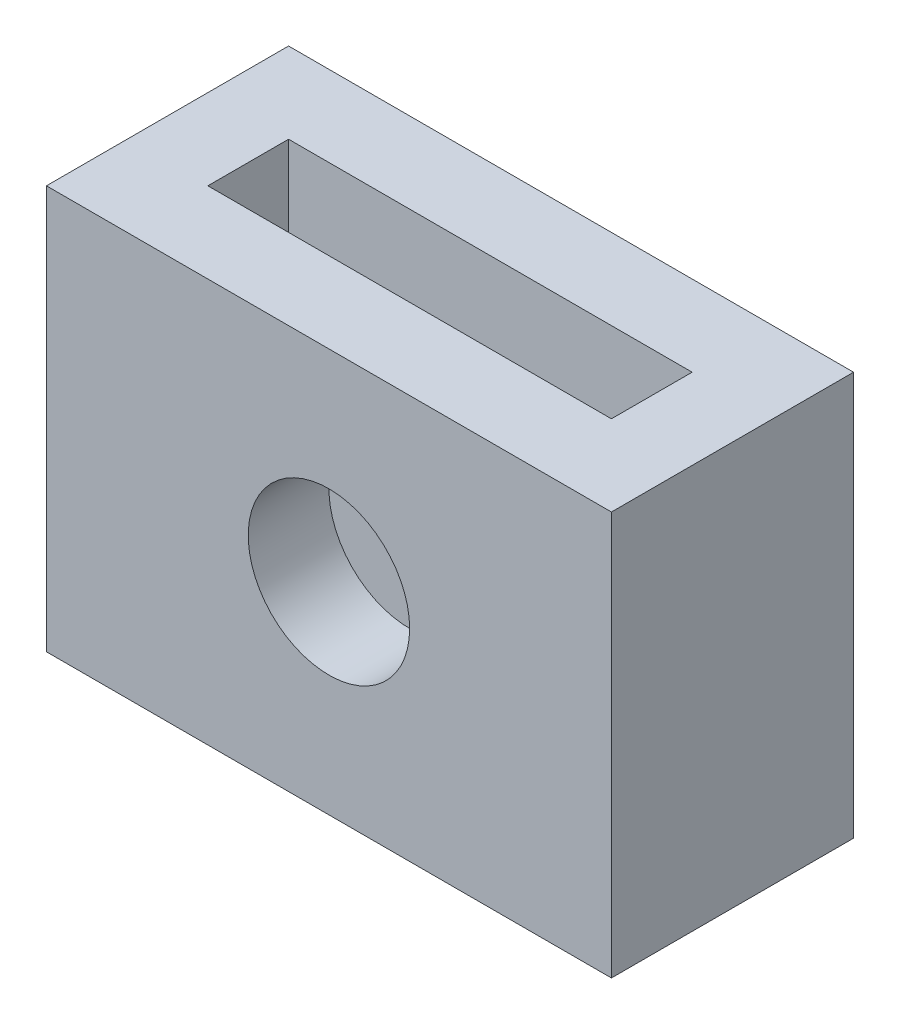
SolidWorks part; units mm, degrees
ref_plane "Alzado" through (0, 0, 0) normal (0, 0, 1) x (1, 0, 0)
ref_plane "Planta" through (0, 0, 0) normal (0, 1, 0) x (1, 0, 0)
ref_plane "Vista lateral" through (0, 0, 0) normal (1, 0, 0) x (0, 0, -1)
sketch "Croquis1" plane through (0, 0, 0) normal (0, 0, 1) x (1, 0, 0)
  line L0 (0, 0) -> (70, 0)
  line L1 (70, 0) -> (70, 50)
  line L2 (70, 50) -> (0, 50)
  line L3 (0, 50) -> (0, 0)
  dimension "D1" = 70
  dimension "D2" = 50
extrude "Saliente-Extruir1" add sketch "Croquis1" along normal blind 30
sketch "Croquis3" plane through (0, 0, 0) normal (0, 1, 0) x (1, 0, 0)
  line L0 (0, 0) -> (10, 0) construction
  line L1 (70, 0) -> (0, 0) construction
  line L2 (10, 0) -> (10, -10) construction
  line L3 (10, -10) -> (60, -10)
  line L4 (60, -10) -> (60, -20)
  line L5 (60, -20) -> (10, -20)
  line L6 (10, -20) -> (10, -10)
  dimension "D1" = 10
  dimension "D2" = 10
  dimension "D3" = 50
  dimension "D4" = 10
extrude "Cortar-Extruir1" cut sketch "Croquis3" along normal blind 67
sketch "Croquis4" plane through (0, 0, 30) normal (0, 0, 1) x (1, 0, 0)
  line L0 (70, 50) -> (0, 50) construction
  line L1 (70, 0) -> (70, 50) construction
  circle A0 centre (35, 25) radius 10
  dimension "D3" = 20
  dimension "D1" = 35
  dimension "D2" = 25
extrude "Cortar-Extruir2" cut sketch "Croquis4" against normal blind 10
